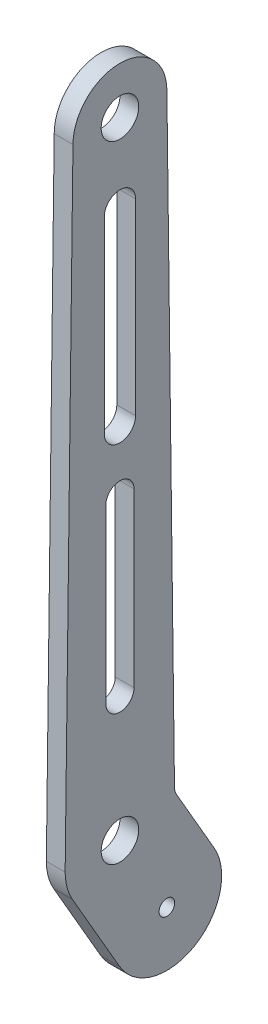
SolidWorks part; units mm, degrees
ref_plane "Front Plane" through (0, 0, 0) normal (0, 0, 1) x (1, 0, 0)
ref_plane "Top Plane" through (0, 0, 0) normal (0, 1, 0) x (1, 0, 0)
ref_plane "Right Plane" through (0, 0, 0) normal (1, 0, 0) x (0, 0, -1)
sketch "草图1" plane through (0, 0, 0) normal (1, 0, 0) x (0, 0, -1)
  line L0 (0, 0) -> (0, -200) construction
  line L1 (15, 0) -> (17.5, -200)
  line L2 (-17.5, -200) -> (-15, 0)
  arc A0 (15, 0) -> (-15, 0) centre (0, 0) ccw
  circle A1 centre (0, 0) radius 6
  arc A2 (-17.5, -200) -> (17.5, -200) centre (0, -200) ccw
  circle A3 centre (0, -200) radius 6
  dimension "D1" = 30
  dimension "D2" = 12
  dimension "D4" = 35
  dimension "D5" = 12
  dimension "D3" = 200
extrude "凸台-拉伸1" add sketch "草图1" along normal blind 6
sketch "草图2" plane through (6, 0, 0) normal (1, 0, 0) x (0, 0, -1)
  line L0 (0, -25) -> (0, -85) construction
  line L2 (5, -25) -> (5, -85)
  line L3 (-5, -25) -> (-5, -85)
  line L4 (0, -105) -> (0, -160) construction
  line L5 (4.5, -105) -> (4.5, -160)
  line L6 (-4.5, -105) -> (-4.5, -160)
  arc A0 (5, -25) -> (-5, -25) centre (0, -25) ccw
  arc A1 (-5, -85) -> (5, -85) centre (0, -85) ccw
  arc A2 (4.5, -105) -> (-4.5, -105) centre (0, -105) ccw
  arc A3 (-4.5, -160) -> (4.5, -160) centre (0, -160) ccw
  point P5 (0, -55)
  point P10 (0, -132.5)
  dimension "D1" = 25
  dimension "D3" = 20
  dimension "D2" = 60
  dimension "D4" = 55
extrude "切除-拉伸1" cut sketch "草图2" against normal blind 10
sketch "草图3" plane through (6, 0, 0) normal (1, 0, 0) x (0, 0, -1)
  line L0 (0, 0) -> (0, -200)
  line L1 (0, -200) -> (15, -225.9808)
  line L2 (-15.1554, -208.75) -> (-0.1554, -234.7308)
  line L3 (15.1554, -191.25) -> (30.1554, -217.2308)
  line L4 (15, 0) -> (17.5, -200)
  circle A0 centre (15, -225.9808) radius 2.5
  circle A1 centre (15, -225.9808) radius 17.5
  arc A2 (-17.5, -200) -> (17.5, -200) centre (0, -200) ccw construction
  circle A3 centre (0, -200) radius 17.5
  dimension "D3" = 5
  dimension "D4" = 35
  dimension "D5" = 35
  dimension "D1" = 30
  dimension "D2" = 150
extrude "凸台-拉伸2" add sketch "草图3" against normal blind 6
fillet "圆角2" radius 5 1 edges at (3, -195.2071, -17.4401)
